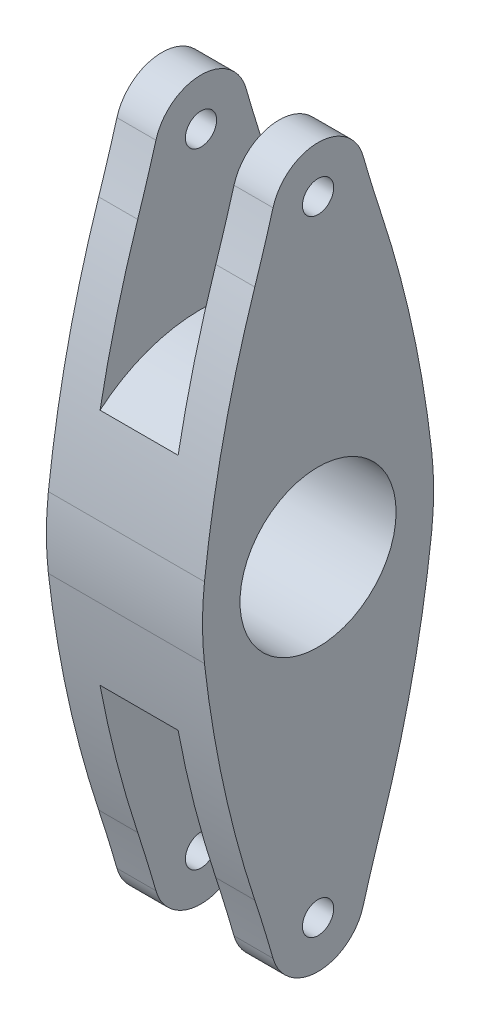
SolidWorks part; units mm, degrees
material "PLA"
ref_plane "Alzado" through (0, 0, 0) normal (0, 0, 1) x (1, 0, 0)
ref_plane "Planta" through (0, 0, 0) normal (0, 1, 0) x (1, 0, 0)
ref_plane "Vista lateral" through (0, 0, 0) normal (1, 0, 0) x (0, 0, -1)
sketch "Croquis1" plane through (0, 0, 0) normal (1, 0, 0) x (0, 0, -1)
  line L0 (0, 0) -> (0, 10) construction
  line L1 (0, 0) -> (0, -10) construction
  line L2 (-2.5, 0) -> (2.5, 0) construction
  circle A0 centre (0, 0) radius 2.5
  circle A2 centre (0, 10) radius 0.5
  arc A3 (-1.5, -10) -> (1.5, -10) centre (0, -10) ccw
  arc A4 (1.5, 10) -> (-1.5, 10) centre (0, 10) ccw
  circle A5 centre (0, -10) radius 0.5
  arc A6 (-3.75, 0) -> (-1.5, -10) centre (33.3048, 3.0842) ccw
  arc A7 (3.75, 0) -> (1.5, -10) centre (-33.3048, 3.0842) cw
  arc A8 (3.75, 0) -> (1.5, 10) centre (-33.3048, -3.0842) ccw
  arc A9 (-3.75, 0) -> (-1.5, 10) centre (33.3048, -3.0842) cw
  dimension "D1" = 5
  dimension "D5" = 1
  dimension "D6" = 3
  dimension "D8" = 1
  dimension "D3" = 10
  dimension "D4" = 10
extrude "Saliente-Extruir1" add sketch "Croquis1" along normal blind 5
fillet "Redondeo1" radius 50 4 edges at (2.5, -10, -1.5) (2.5, -10, 1.5) (2.5, 10, 1.5) (2.5, 10, -1.5)
fillet "Redondeo2" radius 10 2 edges at (2.5, 0, 3.75) (2.5, 0, -3.75)
sketch "Croquis2" plane through (0, 0, 0) normal (-1, 0, 0) x (0, 0, 1)
  arc A1 (-3.2326, -3.8145) -> (3.2326, -3.8145) centre (0, 0) ccw
  arc A2 (3.2326, 3.8145) -> (-3.2326, 3.8145) centre (0, 0) ccw
  arc A14 (2.0261, -8.5045) -> (3.638, -1.1346) centre (-33.3048, 3.0842) ccw
  arc A15 (3.638, -1.1346) -> (3.638, 1.1346) centre (-6.2974, 0) ccw
  arc A16 (3.638, 1.1346) -> (2.0261, 8.5045) centre (-33.3048, -3.0842) ccw
  arc A17 (1.4428, 10.4103) -> (2.0261, 8.5045) centre (49.5357, 24.0879) ccw
  arc A18 (1.4428, 10.4103) -> (-1.4428, 10.4103) centre (0, 10) ccw
  arc A19 (-2.0261, 8.5045) -> (-1.4428, 10.4103) centre (-49.5357, 24.0879) ccw
  arc A20 (-2.0261, 8.5045) -> (-3.638, 1.1346) centre (33.3048, -3.0842) ccw
  arc A21 (-3.638, 1.1346) -> (-3.638, -1.1346) centre (6.2974, 0) ccw
  arc A22 (-3.638, -1.1346) -> (-2.0261, -8.5045) centre (33.3048, 3.0842) ccw
  arc A23 (-1.4428, -10.4103) -> (-2.0261, -8.5045) centre (-49.5357, -24.0879) ccw
  arc A24 (-1.4428, -10.4103) -> (1.4428, -10.4103) centre (0, -10) ccw
  arc A25 (2.0261, -8.5045) -> (1.4428, -10.4103) centre (49.5357, -24.0879) ccw
  arc A26 (2.0261, -8.5045) -> (3.2326, -3.8145) centre (-33.3048, 3.0842) ccw
  arc A28 (3.2326, 3.8145) -> (2.0261, 8.5045) centre (-33.3048, -3.0842) ccw
  arc A29 (1.4428, 10.4103) -> (2.0261, 8.5045) centre (49.5357, 24.0879) ccw
  arc A30 (1.4428, 10.4103) -> (-1.4428, 10.4103) centre (0, 10) ccw
  arc A31 (-2.0261, 8.5045) -> (-1.4428, 10.4103) centre (-49.5357, 24.0879) ccw
  arc A32 (-2.0261, 8.5045) -> (-3.2326, 3.8145) centre (33.3048, -3.0842) ccw
  arc A34 (-3.2326, -3.8145) -> (-2.0261, -8.5045) centre (33.3048, 3.0842) ccw
  arc A35 (-1.4428, -10.4103) -> (-2.0261, -8.5045) centre (-49.5357, -24.0879) ccw
  arc A36 (-1.4428, -10.4103) -> (1.4428, -10.4103) centre (0, -10) ccw
  arc A37 (2.0261, -8.5045) -> (1.4428, -10.4103) centre (49.5357, -24.0879) ccw
  dimension "D1" = 10
  dimension "D2" = 0
extrude "Cortar-Extruir1" cut sketch "Croquis2" against normal mid plane 2.5 from offset 2.5
